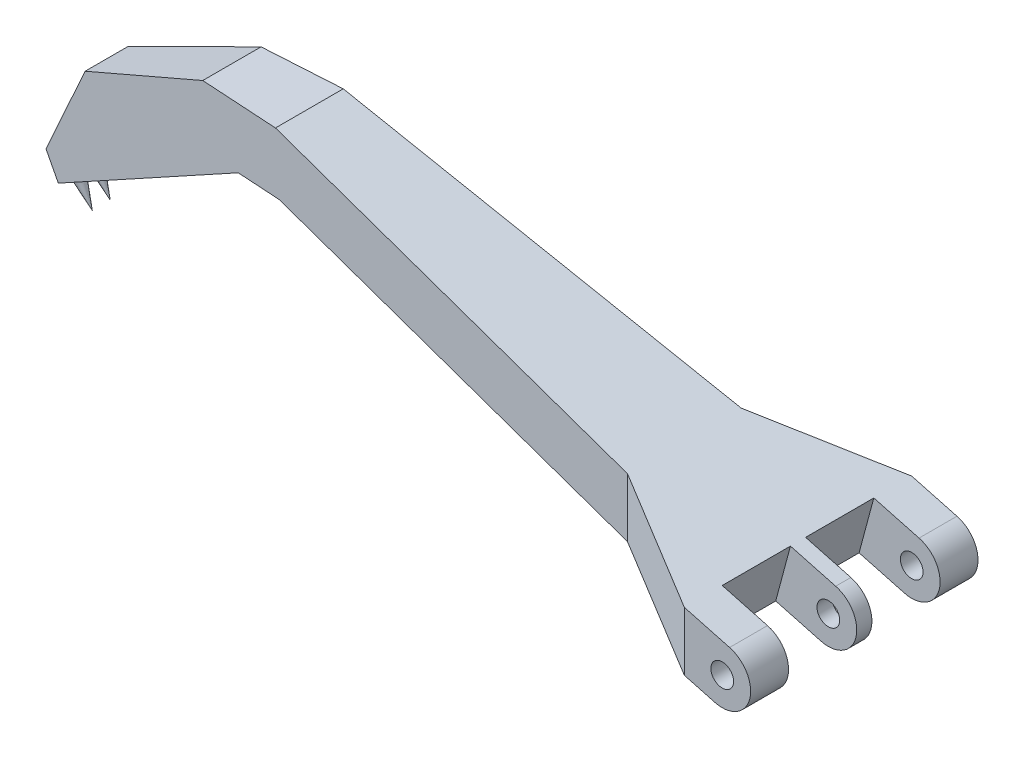
SolidWorks part; units mm, degrees
ref_plane "Front Plane" through (0, 0, 0) normal (0, 0, 1) x (1, 0, 0)
ref_plane "Top Plane" through (0, 0, 0) normal (0, 1, 0) x (1, 0, 0)
ref_plane "Right Plane" through (0, 0, 0) normal (1, 0, 0) x (0, 0, -1)
sketch "Sketch3" plane through (0, 0, 0) normal (0, 0, 1) x (1, 0, 0)
  line L0 (0.9706, 3.6222) -> (-69.4823, 22.5)
  line L1 (-69.4823, 22.5) -> (-79.7011, 22.5)
  line L2 (-79.7011, 22.5) -> (-96.234, 14.7906)
  line L3 (-96.234, 14.7906) -> (-101.7321, 3)
  line L4 (-101.7321, 3) -> (-100, 0)
  line L5 (-100, 0) -> (-74.715, 14.5983)
  line L6 (-74.715, 14.5983) -> (-68.9706, 14.5983)
  line L7 (-68.9706, 14.5983) -> (-0.9706, -3.6222)
  line L8 (-0.9706, -3.6222) -> (0.9706, 3.6222) construction
  line L9 (-5.6356, -2.3722) -> (-3.6945, 4.8722) construction
  line L10 (-100, 0) -> (0, 0) construction
  circle A0 centre (0, 0) radius 1.5
  arc A2 (-0.9706, -3.6222) -> (0.9706, 3.6222) centre (0, 0) ccw
  point P14 (-5, 0)
  dimension "D2" = 3
  dimension "D1" = 100
  dimension "D3" = 7.5
  dimension "D4" = 68
  dimension "D5" = 30
  dimension "D6" = 15
  dimension "D7" = 125
  dimension "D8" = 5.498
  dimension "D9" = 3
  dimension "D10" = 155
  dimension "D11" = 22.5
sketch "Sketch4" plane through (0, 0, 0) normal (1, 0, 0) x (0, 0, -1)
  line L0 (-15, 0) -> (15, 0)
  point P4 (0, 0)
  dimension "D1" = 30
ref_plane "Plane1" through (-101.7321, 0, 0) normal (1, 0, 0) x (0, 0, -1)
sketch "Sketch5" plane through (-101.7321, 0, 0) normal (1, 0, 0) x (0, 0, -1)
  line L0 (2.5, 0) -> (-2.5, 0)
  point P4 (0, 0)
  dimension "D1" = 5
sketch "Sketch14" plane through (0, 0, 0) normal (0, 0, 1) x (1, 0, 0)
  line L0 (-153.9208, -162.5929) -> (-22.7793, -162.5929) construction
extrude "Boss-Extrude2" add sketch "Sketch3" along direction (0, 0, -1) on the side against the normal up to vertex (15 mm away) and the other way up to vertex (15 mm away)
sketch "Sketch12" plane through (0, 0, 0) normal (0, 1, 0) x (1, 0, 0)
  line L0 (-101.7321, 2.5) -> (-101.7321, -2.5) construction
  line L1 (-101.7321, 2.5) -> (-5, 2.5) construction
  line L2 (-101.7321, 2.5) -> (-101.7321, -2.5)
  line L3 (-5, -15) -> (-5, 15)
  line L4 (-101.7321, 2.5) -> (-5, 15) construction
  line L5 (-101.7321, -2.5) -> (-5, -15) construction
  line L6 (-101.7321, 0) -> (0, 0) construction
  line L7 (0, -15) -> (0, 15) construction
  line L8 (0, -15) -> (0, 15) construction
  line L9 (-101.7321, 2.5) -> (-20, 7.5)
  line L10 (-20, 7.5) -> (-5, 15)
  line L11 (-20, -7.5) -> (-5, -15)
  line L12 (-101.7321, -2.5) -> (-20, -7.5)
  dimension "D1" = 5
  dimension "D2" = 7.5
  dimension "D3" = 15
extrude "Cut-Extrude2" cut sketch "Sketch12" along normal through all and the other way through all flip side to cut contours L2 L12 L11 L3 L10 L9
sketch "Sketch13" plane through (0, 0, 0) normal (0, 0, 1) x (1, 0, 0)
  line L0 (-5, 5.222) -> (-5, -2.5425) construction
  line L1 (-5, 5.222) -> (-5, -2.5425)
  line L8 (0.9706, 3.6222) -> (-5, 5.222)
  line L9 (-0.9706, -3.6222) -> (-5, -2.5425)
  arc A0 (-0.9706, -3.6222) -> (0.9706, 3.6222) centre (0, 0) ccw construction
  circle A1 centre (0, 0) radius 1.5 construction
  arc A2 (-0.9706, -3.6222) -> (0.9706, 3.6222) centre (0, 0) ccw
  circle A3 centre (0, 0) radius 1.5
extrude "Boss-Extrude3" add sketch "Sketch13" along direction (0, 0, 1) on the side of the normal up to vertex (15 mm away) and the other way up to vertex (15 mm away)
sketch "Sketch16" plane through (0.9706, 3.6222, 0) normal (0.2588, 0.9659, 0) x (0.9659, -0.2588, 0)
  line L0 (3.75, -15) -> (3.75, 15) construction
  line L1 (3.75, -15) -> (3.75, 15) construction
  line L2 (3.75, 15) -> (0, 15) construction
  line L3 (0, -15) -> (3.75, -15) construction
  line L4 (3.75, 15) -> (0, 15) construction
  line L5 (0, -15) -> (3.75, -15) construction
  line L6 (0, 15) -> (-6.1812, 15) construction
  line L7 (0, -15) -> (-6.1812, -15) construction
  line L8 (0, 15) -> (-6.1812, 15) construction
  line L9 (0, -15) -> (-6.1812, -15) construction
  line L10 (-6.1812, -15) -> (-6.1812, 15) construction
  line L11 (3.75, 0) -> (-6.1812, 0) construction
  line L12 (3.75, -1) -> (-6.1812, -1)
  line L13 (-6.1812, 1) -> (3.75, 1)
  line L14 (-6.1812, -10) -> (3.75, -10)
  line L15 (-6.1812, 10) -> (3.75, 10)
  line L16 (3.75, -10) -> (-6.1812, -10)
  line L17 (-6.1812, -10) -> (-6.1812, -1)
  line L18 (3.75, -1) -> (3.75, -10)
  line L19 (-6.1812, 10) -> (-6.1812, 1)
  line L20 (3.75, 1) -> (3.75, 10)
  line L21 (3.75, -1) -> (3.75, -10)
  line L22 (-6.1812, -10) -> (-6.1812, -1)
  line M12 (0, -15) -> (0, 15)
  dimension "D1" = 2
  dimension "D2" = 9
extrude "Cut-Extrude8" cut sketch "Sketch16" against normal up to surface (7.5 mm away) contours L15 L19 L13 M12 | L17 L14 L12 M12 | L18 L12 L14 M12 | L13 L20 L15 M12 up to face at (-23.7353, 2.4776, 0)
sketch "Sketch17" plane through (-25, 43.3013, 0) normal (0.5, -0.866, 0) x (0.866, 0.5, 0)
  line L0 (-86.6025, 0) -> (-57.4059, 0) construction
  line L1 (-86.6025, -2.606) -> (-86.6025, 2.606) construction
  line L2 (-57.4059, -4.1528) -> (-57.4059, 4.1528) construction
  line L3 (-86.6025, 2.606) -> (-57.4059, 4.1528) construction
  circle A0 centre (-85.1025, 1.1833) radius 0.75
  circle A1 centre (-85.1025, -1.1833) radius 0.75
  dimension "D1" = 1.5
  dimension "D2" = 1.5
  dimension "D3" = 1.5
extrude "Boss-Extrude4" add sketch "Sketch17" along normal blind 6 draft 12
